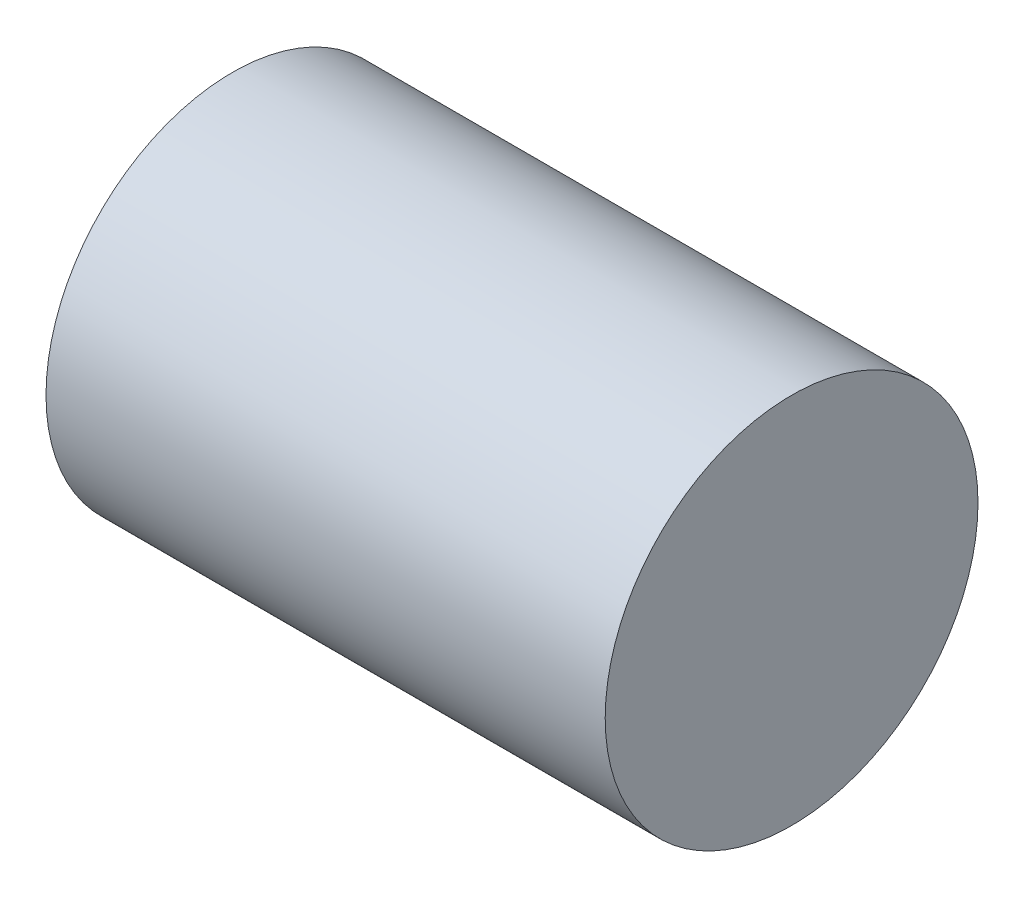
SolidWorks part; units mm, degrees
material "AISI 304"
ref_plane "Front Plane" through (0, 0, 0) normal (0, 0, 1) x (1, 0, 0)
ref_plane "Top Plane" through (0, 0, 0) normal (0, 1, 0) x (1, 0, 0)
ref_plane "Right Plane" through (0, 0, 0) normal (1, 0, 0) x (0, 0, -1)
sketch "Croquis1" plane through (0, 0, 0) normal (1, 0, 0) x (0, 0, -1)
  circle A0 centre (0, 0) radius 10
  dimension "D1" = 20
extrude "Saliente-Extruir1" add sketch "Croquis1" against normal blind 30
